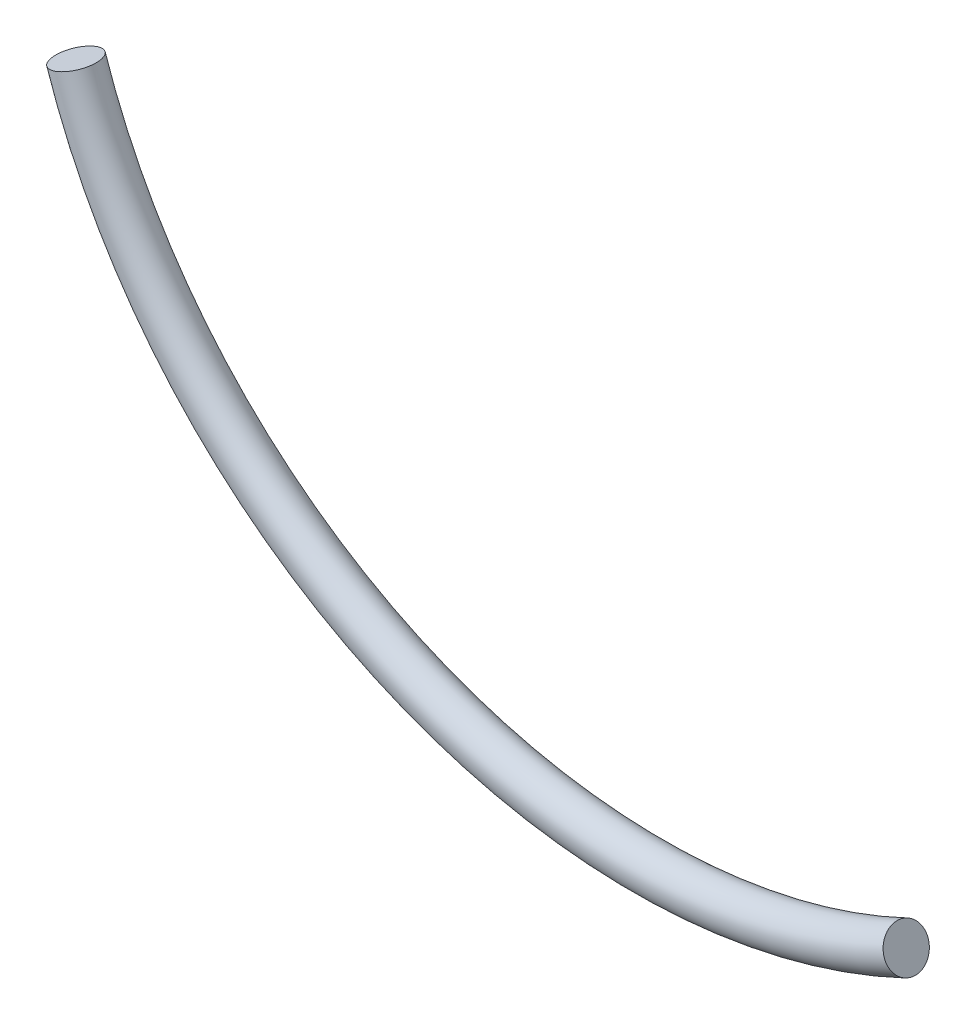
SolidWorks part; units mm, degrees
ref_plane "Front" through (0, 0, 0) normal (0, 0, 1) x (1, 0, 0)
ref_plane "Top" through (0, 0, 0) normal (0, 1, 0) x (1, 0, 0)
ref_plane "Right" through (0, 0, 0) normal (1, 0, 0) x (0, 0, -1)
sketch "Sketch1" plane through (0, 0, 0) normal (0, 0, 1) x (1, 0, 0)
  arc A0 (1640.1048, -2343.3491) -> (3623.9082, -3191.1987) centre (3006.9834, -1889.9007) ccw
  spline S0 degree 3 poles (12.6287, -1542.4185) (1660.0512, -1247.4612) (1396.184, -2572.0697) (2552.1536, -3378.376) (3653.2248, -3381.0744) (4498.8593, -2410.0471) (4234.3259, -1332.1122) (3828.4317, -438.5455) (2878.5173, 34.0308) (1828.4268, -38.3903) (848.7491, -832.9542) (478.3486, -2168.9227) (655.66, -3702.3879) (1776.0331, -4731.1943) (3233.2155, -4916.8204) (4680.4296, -4726.8399) (6307.3282, -3696.4175) (7469.1656, -2286.7006) (7106.2538, 15.9001) (6390.1027, 1605.915) (4943.9608, 2829.7833) (3528.655, 3564.3804) (2398.2908, 3971.4721) (81.6978, 4346.5877) (-2107.3471, 3741.776) (-3307.6994, 3064.2218) (-4872.4252, 2142.1063) (-6051.5753, 670.5262) (-6903.7379, -1042.8518) (-6660.4419, -2913.7021) (-4530.0051, -4010.9344) (-3278.8488, -4392.9339) (-2255.8989, -4955.8268) knots -0.03564 -0.03564 -0.03564 -0.03564 0.012418 0.026176 0.053223 0.077498 0.099256 0.122387 0.140197 0.165808 0.187601 0.21914 0.254189 0.284814 0.311917 0.350124 0.381709 0.440659 0.47622 0.524804 0.564919 0.59506 0.63529 0.679111 0.741875 0.781701 0.810098 0.866605 0.901783 0.935896 0.978749 1.043408 1.043408 1.043408 1.043408 only from (1640.1048, -2343.3491) to (-4072.3026, -4122.4591) construction
  dimension "D1" = 2438.4
ref_plane "Plane1" through (1640.1048, -2343.3491, 0) normal (0.3149, -0.9491, 0) x (0.9491, 0.3149, 0)
sketch "Sketch2" plane through (1640.1048, -2343.3491, 0) normal (0.3149, -0.9491, 0) x (0.9491, 0.3149, 0)
  circle A0 centre (0, 0) radius 50.8
  dimension "D1" = 101.6
sweep "Sweep1" add profiles "Sketch2" path "Sketch1"
